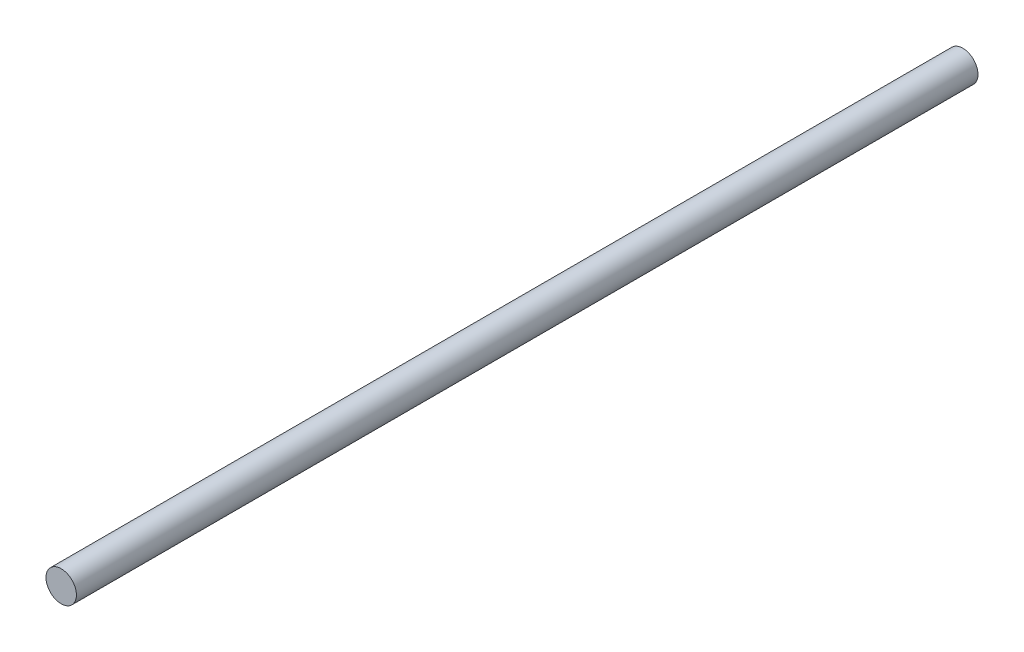
SolidWorks part; units mm, degrees
ref_plane "Front Plane" through (0, 0, 0) normal (0, 0, 1) x (1, 0, 0)
ref_plane "Top Plane" through (0, 0, 0) normal (0, 1, 0) x (1, 0, 0)
ref_plane "Right Plane" through (0, 0, 0) normal (1, 0, 0) x (0, 0, -1)
sketch "Sketch1" plane through (0, 0, 0) normal (0, 0, 1) x (1, 0, 0)
  circle A0 centre (0, 0) radius 6
  dimension "D1" = 12
extrude "Boss-Extrude1" add sketch "Sketch1" along normal blind 355.6
